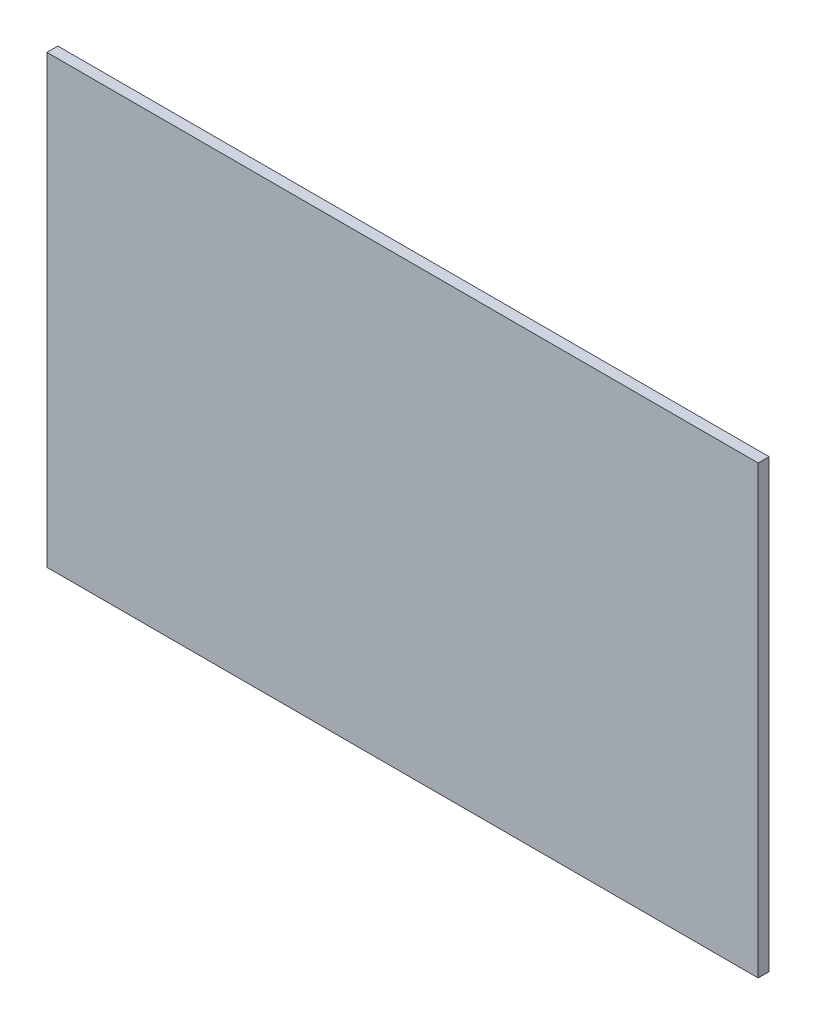
SolidWorks part; units mm, degrees
ref_plane "前基準面" through (0, 0, 0) normal (0, 0, 1) x (1, 0, 0)
ref_plane "上基準面" through (0, 0, 0) normal (0, 1, 0) x (1, 0, 0)
ref_plane "右基準面" through (0, 0, 0) normal (1, 0, 0) x (0, 0, -1)
sketch "草圖1" plane through (0, 0, 0) normal (0, 0, 1) x (1, 0, 0)
  line L1 (-73.1561, 37.7825) -> (56.8439, 37.7825)
  line L2 (-73.1561, 37.7825) -> (-73.1561, -43.7198)
  line L3 (-73.1561, -43.7198) -> (56.8439, -43.7198)
  line L4 (56.8439, 37.7825) -> (56.8439, -43.7198)
extrude "填料-伸長1" add sketch "草圖1" along normal blind 2
